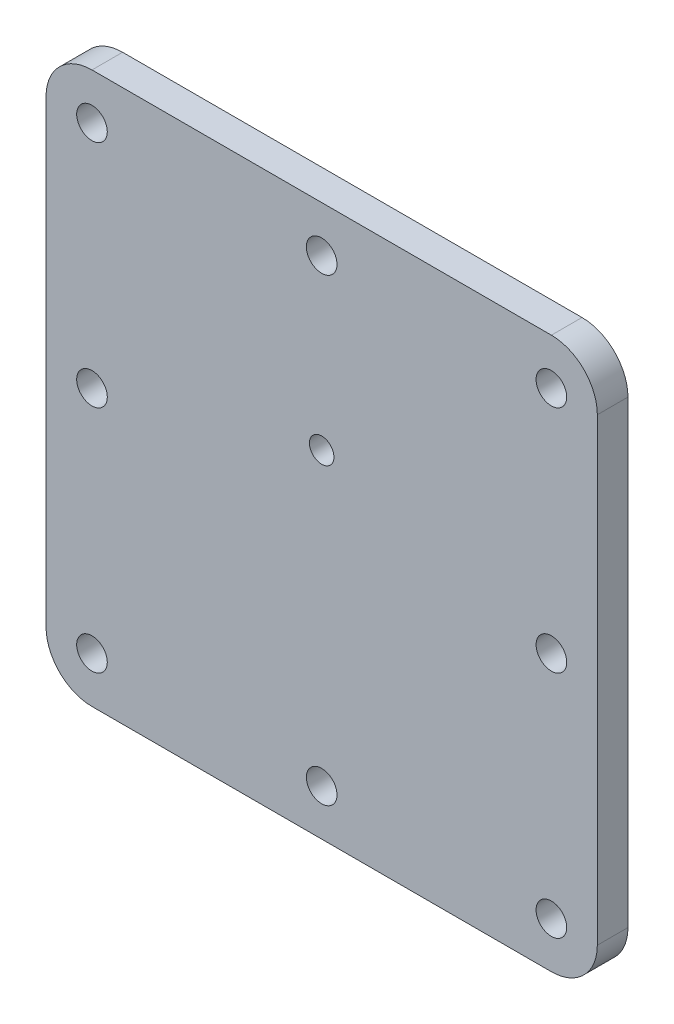
SolidWorks part; units mm, degrees
ref_plane "Front Plane" through (0, 0, 0) normal (0, 0, 1) x (1, 0, 0)
ref_plane "Top Plane" through (0, 0, 0) normal (0, 1, 0) x (1, 0, 0)
ref_plane "Right Plane" through (0, 0, 0) normal (1, 0, 0) x (0, 0, -1)
sketch "Sketch2" plane through (0, 0, 0) normal (0, 0, 1) x (1, 0, 0)
  line L0 (-75, 75) -> (75, 75) construction
  line L1 (-75, 90) -> (75, 90)
  line L2 (-90, 75) -> (-90, -75)
  line L3 (-75, -90) -> (75, -90)
  line L4 (90, 75) -> (90, -75)
  line L5 (-90, 90) -> (90, -90) construction
  line L6 (-90, -90) -> (90, 90) construction
  line L7 (75, 75) -> (75, -75) construction
  line L8 (75, -75) -> (-75, -75) construction
  line L9 (-75, -75) -> (-75, 75) construction
  line L15 (-60, 60) -> (60, -60) construction
  line L16 (-60, -60) -> (60, 60) construction
  arc A0 (-90, -75) -> (-75, -90) centre (-75, -75) ccw
  arc A1 (75, -90) -> (90, -75) centre (75, -75) ccw
  arc A2 (75, 90) -> (90, 75) centre (75, 75) cw
  arc A3 (-75, 90) -> (-90, 75) centre (-75, 75) ccw
  circle A4 centre (-75, 75) radius 5
  circle A5 centre (0, 75) radius 5
  circle A6 centre (75, 75) radius 5
  circle A7 centre (-75, 0) radius 5
  circle A8 centre (0, 0) radius 5 construction
  circle A9 centre (75, 0) radius 5
  circle A10 centre (-75, -75) radius 5
  circle A11 centre (0, -75) radius 5
  circle A12 centre (75, -75) radius 5
  point P0 (0, 0)
  dimension "D3" = 15
  dimension "D4" = 10
  dimension "D1" = 180
  dimension "D2" = 180
  dimension "D8" = 120
  dimension "D7" = 3
extrude "Boss-Extrude1" add sketch "Sketch2" along normal blind 10
sketch "Sketch3" plane through (0, 0, 10) normal (0, 0, 1) x (1, 0, 0)
  line L1 (-50, 50) -> (50, 50) construction
  line L2 (-50, 50) -> (-50, -50) construction
  line L3 (-50, -50) -> (50, -50) construction
  line L4 (50, 50) -> (50, -50) construction
  line L5 (-50, 50) -> (50, -50) construction
  line L6 (-50, -50) -> (50, 50) construction
  line L7 (0, 0) -> (-40, 0) construction
  line L8 (0, 0) -> (0, 40) construction
  line L9 (0, 40) -> (-40, 40) construction
  line L10 (-40, 0) -> (-40, 40) construction
  circle A0 centre (0, 0) radius 4 construction
  point P0 (0, 0)
  dimension "D5" = 8
  dimension "D1" = 100
  dimension "D2" = 100
  dimension "D3" = 40
  dimension "D4" = 40
sketch "Sketch5" plane through (0, 0, 10) normal (0, 0, 1) x (1, 0, 0)
  line L0 (0, 0) -> (0, 40) construction
  circle A0 centre (0, 20) radius 4
  dimension "D1" = 8
extrude "Cut-Extrude3" cut sketch "Sketch5" against normal blind 10
